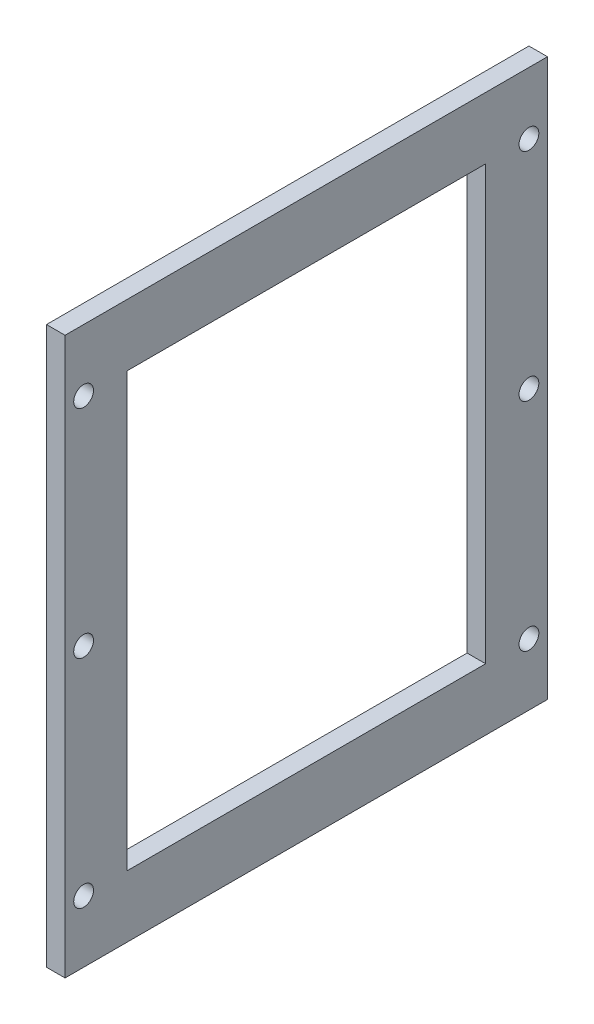
SolidWorks part; units mm, degrees
ref_plane "前视基准面" through (0, 0, 0) normal (0, 0, 1) x (1, 0, 0)
ref_plane "上视基准面" through (0, 0, 0) normal (0, 1, 0) x (1, 0, 0)
ref_plane "右视基准面" through (0, 0, 0) normal (1, 0, 0) x (0, 0, -1)
other "Configuration Table"
sketch "草图1" plane through (0, 0, 0) normal (1, 0, 0) x (0, 0, -1)
  line L0 (0, 225) -> (0, 0) construction
  line L1 (-145, 175) -> (145, 175)
  line L2 (-145, 175) -> (-145, -175)
  line L3 (-145, -175) -> (145, -175)
  line L4 (145, 175) -> (145, -175)
  line L5 (-145, 175) -> (145, -175) construction
  line L6 (-145, -175) -> (145, 175) construction
  line L7 (-195, 225) -> (195, 225)
  line L8 (-195, 225) -> (-195, -225)
  line L9 (-195, -225) -> (195, -225)
  line L10 (195, 225) -> (195, -225)
  line L11 (-195, 225) -> (195, -225) construction
  line L12 (-195, -225) -> (195, 225) construction
  line L13 (0, 0) -> (-195, 0) construction
  circle A0 centre (-180, 175) radius 8
  circle A1 centre (-180, -175) radius 8
  circle A2 centre (-180, 0) radius 8
  circle A3 centre (180, 175) radius 8
  circle A4 centre (180, 0) radius 8
  circle A5 centre (180, -175) radius 8
  point P0 (0, 0)
  point P6 (0, 0)
  point P20 (0, 0)
  dimension "D6" = 350
  dimension "D7" = 16
  dimension "D1" = 290
  dimension "D2" = 350
  dimension "D3" = 390
  dimension "D4" = 450
  dimension "D5" = 360
extrude "凸台-拉伸1" add sketch "草图1" along normal blind 15
